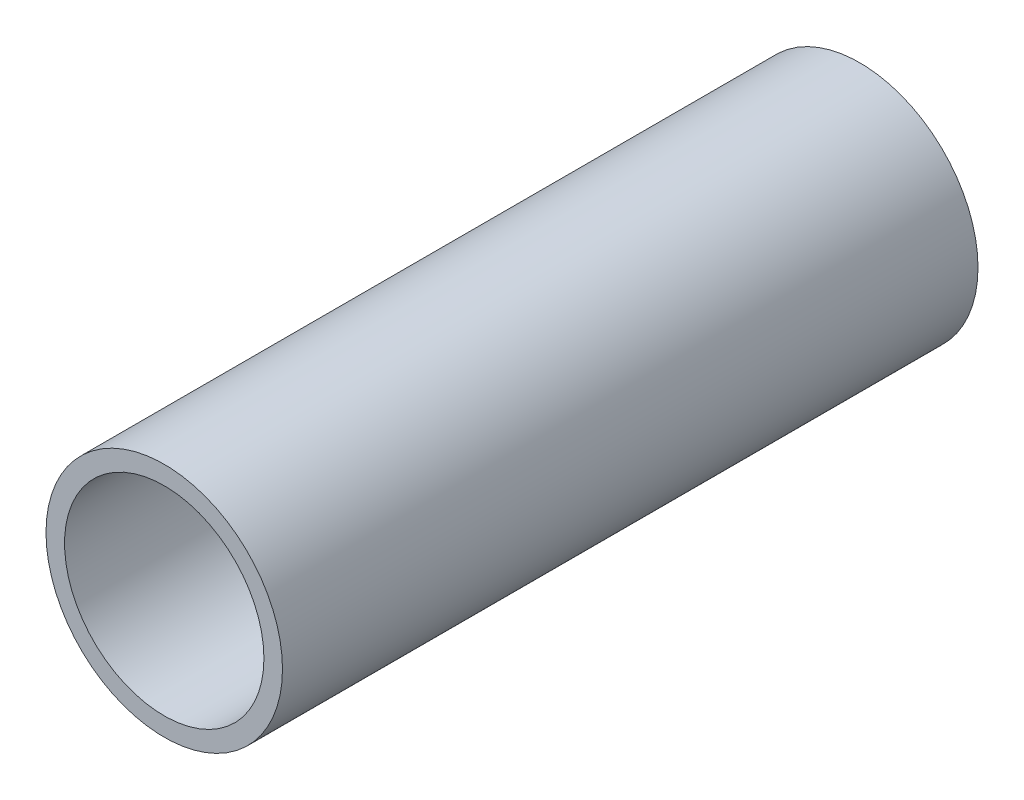
SolidWorks part; units mm, degrees
ref_plane "Front Plane" through (0, 0, 0) normal (0, 0, 1) x (1, 0, 0)
ref_plane "Top Plane" through (0, 0, 0) normal (0, 1, 0) x (1, 0, 0)
ref_plane "Right Plane" through (0, 0, 0) normal (1, 0, 0) x (0, 0, -1)
sketch "Sketch3" plane through (0, 0, 0) normal (0, 0, 1) x (1, 0, 0)
  circle A0 centre (0, 0) radius 2.55
  circle A1 centre (0, 0) radius 2.15
  dimension "D1" = 4.3
  dimension "D2" = 5.1
extrude "Boss-Extrude1" add sketch "Sketch3" along normal blind 15 contours A0 A1
